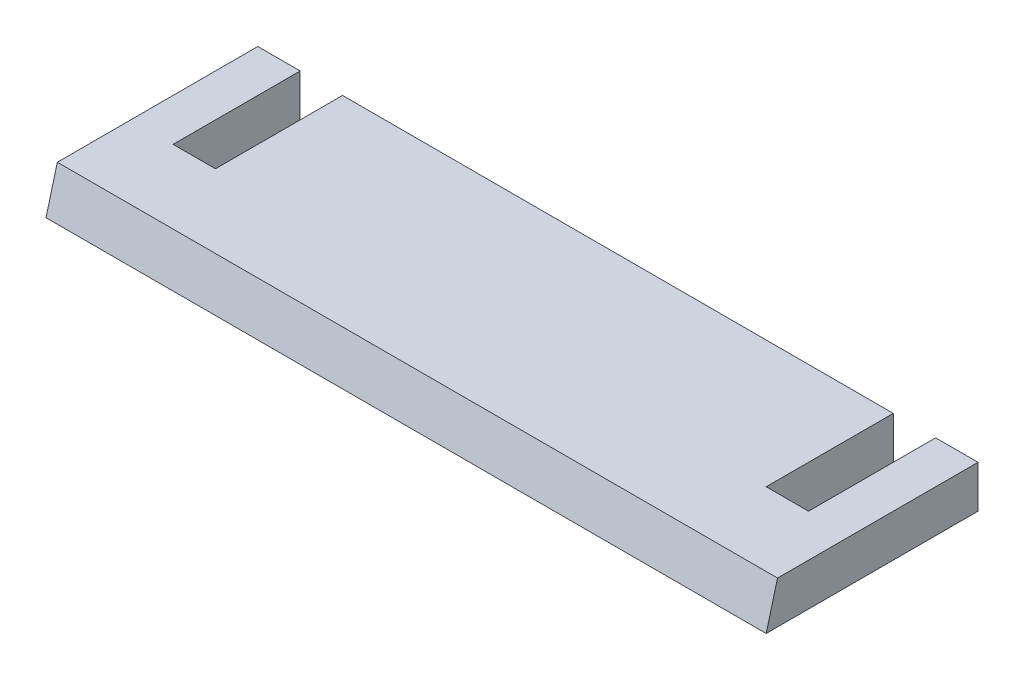
SolidWorks part; units mm, degrees
ref_plane "Front Plane" through (0, 0, 0) normal (0, 0, 1) x (1, 0, 0)
ref_plane "Top Plane" through (0, 0, 0) normal (0, 1, 0) x (1, 0, 0)
ref_plane "Right Plane" through (0, 0, 0) normal (1, 0, 0) x (0, 0, -1)
sketch "Sketch1" plane through (0, 0, 0) normal (0, 1, 0) x (1, 0, 0)
  line L0 (-75, 25) -> (-75, -5)
  line L1 (-85, 25) -> (-75, 25)
  line L2 (-85, 25) -> (-85, -25)
  line L3 (-85, -25) -> (85, -25)
  line L4 (85, 25) -> (85, -25)
  line L5 (-85, 25) -> (85, -25) construction
  line L6 (-85, -25) -> (85, 25) construction
  line L7 (-75, -5) -> (-65, -5)
  line L8 (-65, -5) -> (-65, 25)
  line L9 (0, 38.0601) -> (0, -34.0199) construction
  line L10 (-65, 25) -> (65, 25)
  line L11 (65, -5) -> (65, 25)
  line L12 (75, -5) -> (65, -5)
  line L13 (75, 25) -> (75, -5)
  line L14 (75, 25) -> (85, 25)
  point P0 (0, 0)
  dimension "D1" = 170
  dimension "D2" = 50
  dimension "D3" = 10
  dimension "D4" = 10
  dimension "D5" = 30
extrude "Boss-Extrude1" add sketch "Sketch1" along normal blind 10
draft "Draft2" type of draft neutral plane draft angle 15 faces to draft 1 face at (0, 5, 25) neutral plane through (0, 0, 0) neutral plane normal (0, -1, 0) reverse direction yes parameters "D1"=15
